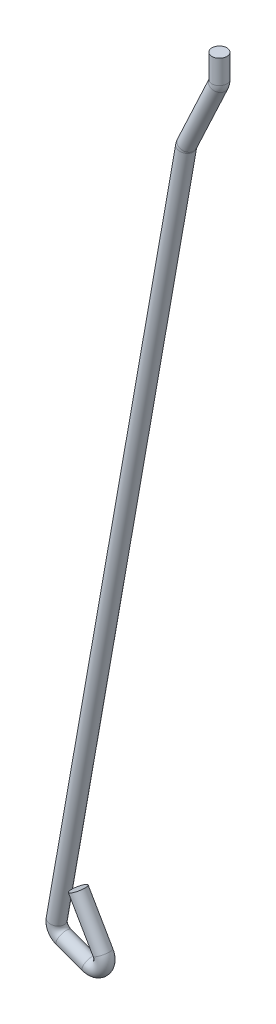
SolidWorks part; units mm, degrees
material "Brass"
ref_plane "Front Plane" through (0, 0, 0) normal (0, 0, 1) x (1, 0, 0)
ref_plane "Top Plane" through (0, 0, 0) normal (0, 1, 0) x (1, 0, 0)
ref_plane "Right Plane" through (0, 0, 0) normal (1, 0, 0) x (0, 0, -1)
sketch "Sketch1" plane through (0, 0, 0) normal (0, 0, 1) x (1, 0, 0)
  line L0 (0, 0) -> (0, -2.8934)
  line L1 (-0.119, -3.4302) -> (-3.9548, -11.656)
  line L2 (-4.0545, -11.9722) -> (-19.829, -101.4343)
  line L3 (-19.0127, -102.8482) -> (-15.8342, -104.0051)
  line L4 (-14.2999, -102.1767) -> (-17.3178, -96.9496)
  arc A0 (-0.119, -3.4302) -> (0, -2.8934) centre (-1.27, -2.8934) ccw
  arc A1 (-4.0545, -11.9722) -> (-3.9548, -11.656) centre (-2.8038, -12.1928) cw
  arc A2 (-19.829, -101.4343) -> (-19.0127, -102.8482) centre (-18.5783, -101.6548) ccw
  arc A3 (-15.8342, -104.0051) -> (-14.2999, -102.1767) centre (-15.3998, -102.8117) ccw
  point P3 (-80.3064, -823.3037)
  point P10 (0, -3.175)
  point P13 (-4.0254, -11.8076)
  point P16 (-20.0141, -102.4838)
  point P19 (-12.5553, -105.1985)
  point P20 (0, 0)
  dimension "D10" = 1.27
  dimension "D1" = 10
  dimension "D2" = 25
  dimension "D3" = 110
  dimension "D4" = 40
  dimension "D5" = 3.175
  dimension "D6" = 9.525
  dimension "D7" = 92.075
  dimension "D8" = 7.9375
  dimension "D9" = 9.525
sketch "Sketch2" plane through (0, 0, 0) normal (0, 1, 0) x (1, 0, 0)
  line L0 (-0.119, 0) -> (0, 0) construction
  circle A0 centre (-0.0595, 0) radius 0.9144
  dimension "D1" = 1.8288
sweep "Sweep3" add profiles "Sketch2" path "Sketch1"
